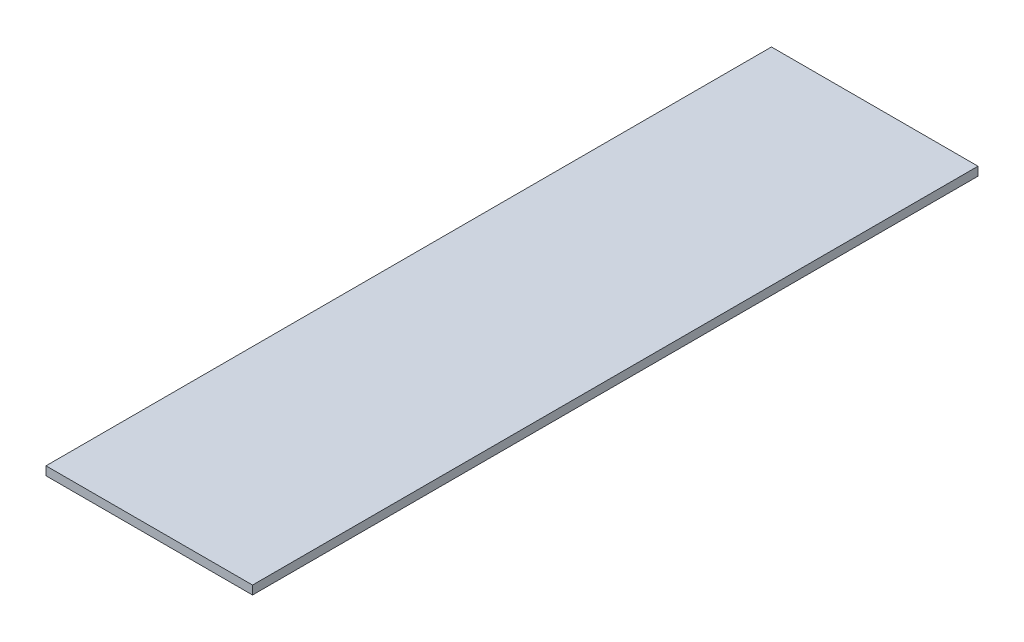
SolidWorks part; units mm, degrees
ref_plane "Спереди" through (0, 0, 0) normal (0, 0, 1) x (1, 0, 0)
ref_plane "Сверху" through (0, 0, 0) normal (0, 1, 0) x (1, 0, 0)
ref_plane "Справа" through (0, 0, 0) normal (1, 0, 0) x (0, 0, -1)
sketch "Эскиз1" plane through (0, 0, 0) normal (0, 1, 0) x (1, 0, 0)
  line L1 (-357.5, 1255.75) -> (357.5, 1255.75)
  line L2 (-357.5, 1255.75) -> (-357.5, -1255.75)
  line L3 (-357.5, -1255.75) -> (357.5, -1255.75)
  line L4 (357.5, 1255.75) -> (357.5, -1255.75)
  line L5 (-357.5, 1255.75) -> (357.5, -1255.75) construction
  line L6 (-357.5, -1255.75) -> (357.5, 1255.75) construction
  point P0 (0, 0)
  dimension "D1" = 715
  dimension "D2" = 2511.5
extrude "Бобышка-Вытянуть1" add sketch "Эскиз1" along normal blind 30
